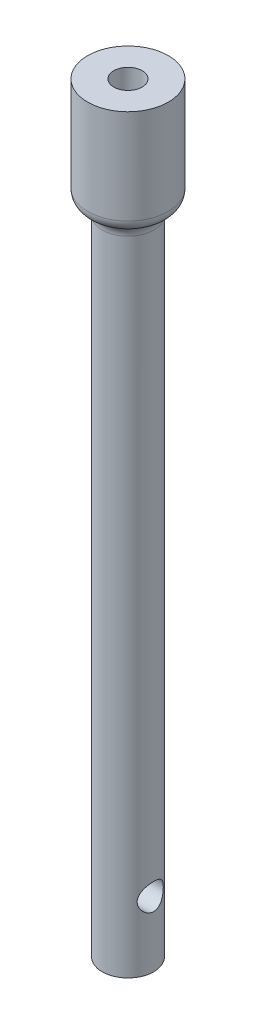
SolidWorks part; units mm, degrees
ref_plane "Front Plane" through (0, 0, 0) normal (0, 0, 1) x (1, 0, 0)
ref_plane "Top Plane" through (0, 0, 0) normal (0, 1, 0) x (1, 0, 0)
ref_plane "Right Plane" through (0, 0, 0) normal (1, 0, 0) x (0, 0, -1)
sketch "Sketch1" plane through (0, 0, 0) normal (0, 0, 1) x (1, 0, 0)
  line L0 (0, 0) -> (-7.9, 0)
  line L1 (-7.9, 0) -> (-7.9, 200)
  line L5 (0, 220) -> (0, 0)
  line L7 (-4.35, 233) -> (-4.35, 220)
  line L8 (-4.35, 220) -> (0, 220)
  line L14 (-12.35, 233) -> (-4.35, 233)
  line L15 (-7.9, 200) -> (-12.35, 200)
  line L16 (-12.35, 200) -> (-12.35, 233)
  point P11 (-12.35, 233)
  point P14 (-7.9, 200)
  dimension "D1" = 7.9
  dimension "D2" = 4.35
  dimension "D3" = 200
  dimension "D4" = 33
  dimension "D5" = 13
  dimension "D6" = 8
revolve "Revolve1" add sketch "Sketch1" angle 360 about L5
sketch "Sketch2" plane through (0, 220, 0) normal (0, 1, 0) x (1, 0, 0)
  line L0 (2.35, 3.6606) -> (2.35, -3.6606)
  line L1 (-4.35, 0) -> (4.35, 0) construction
  circle A0 centre (0, 0) radius 4.35 construction
  circle A3 centre (0, 0) radius 4.35 construction
  point P11 (2.35, 0)
  circle M2 centre (0, 0) radius 4.35
  dimension "D1" = 6.7
extrude "Boss-Extrude1" add sketch "Sketch2" along normal blind 10 contours L1 L0 M2 | L0 L1 M2
sketch "Sketch3" plane through (0, 0, 0) normal (1, 0, 0) x (0, 0, -1)
  line L0 (-7.9, 20) -> (7.9, 20) construction
  line L1 (-7.9, 200) -> (-7.9, 0) construction
  line L4 (-7.9, 0) -> (7.9, 0) construction
  line L5 (7.9, 0) -> (7.9, 200) construction
  circle A1 centre (0, 20) radius 4
  dimension "D1" = 20
  dimension "D2" = 8
extrude "Cut-Extrude1" cut sketch "Sketch3" against normal through all both and the other way through all contours A1
fillet "Fillet1" radius 4 1 edges at (-12.35, 200, 0)
fillet "Fillet2" radius 4 1 edges at (-7.9, 200, 0)
